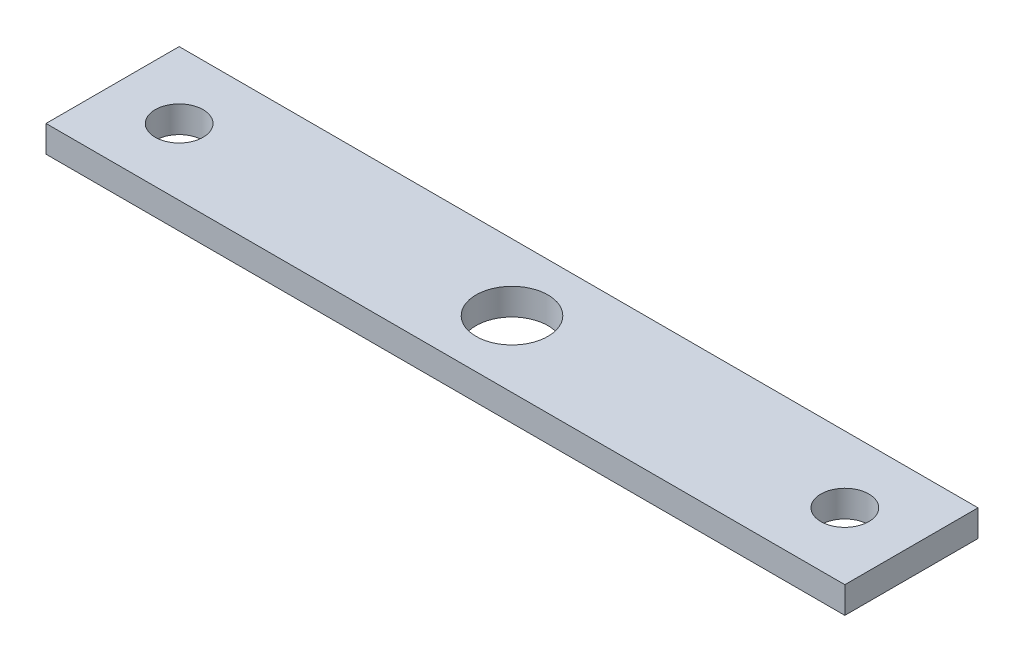
SolidWorks part; units mm, degrees
material "AISI 304"
ref_plane "Front Plane" through (0, 0, 0) normal (0, 0, 1) x (1, 0, 0)
ref_plane "Top Plane" through (0, 0, 0) normal (0, 1, 0) x (1, 0, 0)
ref_plane "Right Plane" through (0, 0, 0) normal (1, 0, 0) x (0, 0, -1)
sketch "Sketch1" plane through (0, 0, 0) normal (0, 1, 0) x (1, 0, 0)
  line L1 (-38.1, 6.35) -> (38.1, 6.35)
  line L2 (-38.1, 6.35) -> (-38.1, -6.35)
  line L3 (-38.1, -6.35) -> (38.1, -6.35)
  line L4 (38.1, 6.35) -> (38.1, -6.35)
  line L5 (-38.1, 6.35) -> (38.1, -6.35) construction
  line L6 (-38.1, -6.35) -> (38.1, 6.35) construction
  circle A0 centre (0, 0) radius 3.429
  circle A1 centre (31.75, 0) radius 2.286
  circle A2 centre (-31.75, 0) radius 2.286
  point P0 (0, 0)
  dimension "D3" = 6.858
  dimension "D4" = 4.572
  dimension "D5" = 4.572
  dimension "D1" = 12.7
  dimension "D2" = 76.2
  dimension "D6" = 31.75
  dimension "D7" = 31.75
  dimension "D8" = 6.35
  dimension "D9" = 6.35
extrude "Boss-Extrude1" add sketch "Sketch1" along normal blind 2.54
